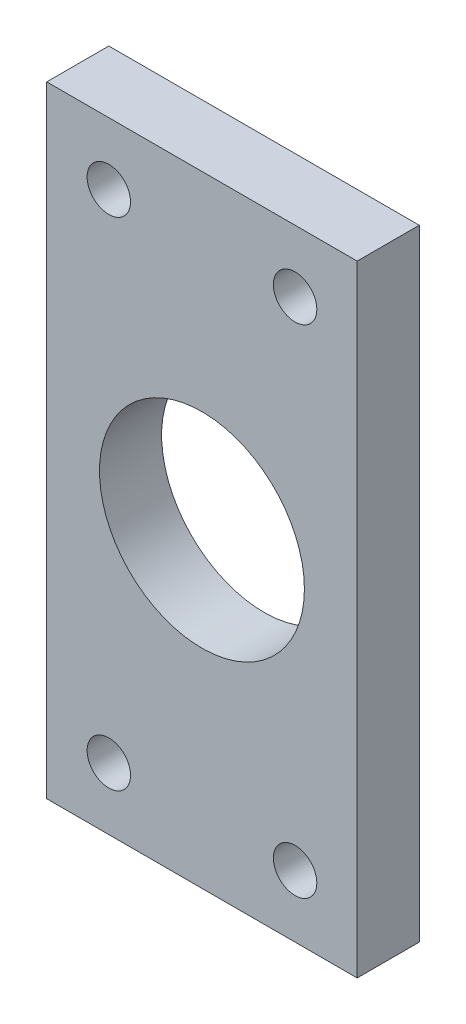
SolidWorks part; units mm, degrees
ref_plane "正面" through (0, 0, 0) normal (0, 0, 1) x (1, 0, 0)
ref_plane "平面" through (0, 0, 0) normal (0, 1, 0) x (1, 0, 0)
ref_plane "右側面" through (0, 0, 0) normal (1, 0, 0) x (0, 0, -1)
sketch "ｽｹｯﾁ1" plane through (0, 0, 0) normal (0, 0, 1) x (1, 0, 0)
  line L0 (-7.5, 20) -> (-7.5, -20) construction
  line L1 (-12.5, 25) -> (12.5, 25)
  line L2 (-12.5, 25) -> (-12.5, -25)
  line L3 (-12.5, -25) -> (12.5, -25)
  line L4 (12.5, 25) -> (12.5, -25)
  line L5 (-12.5, 25) -> (12.5, -25) construction
  line L6 (-12.5, -25) -> (12.5, 25) construction
  line L7 (-7.5, -20) -> (7.5, -20) construction
  line L8 (7.5, 20) -> (7.5, -20) construction
  line L9 (-7.5, 20) -> (7.5, 20) construction
  circle A0 centre (0, 0) radius 8.25
  circle A5 centre (-7.5, 20) radius 1.75
  circle A9 centre (7.5, 20) radius 1.75
  circle A10 centre (-7.5, -20) radius 1.75
  circle A11 centre (7.5, -20) radius 1.75
  point P0 (0, 0)
  dimension "D3" = 16.5
  dimension "D4" = 5
  dimension "D5" = 3.5
  dimension "D6" = 3.5
  dimension "D7" = 3.5
  dimension "D8" = 3.5
  dimension "D1" = 25
  dimension "D2" = 50
extrude "ﾎﾞｽ - 押し出し1" add sketch "ｽｹｯﾁ1" along normal blind 5
